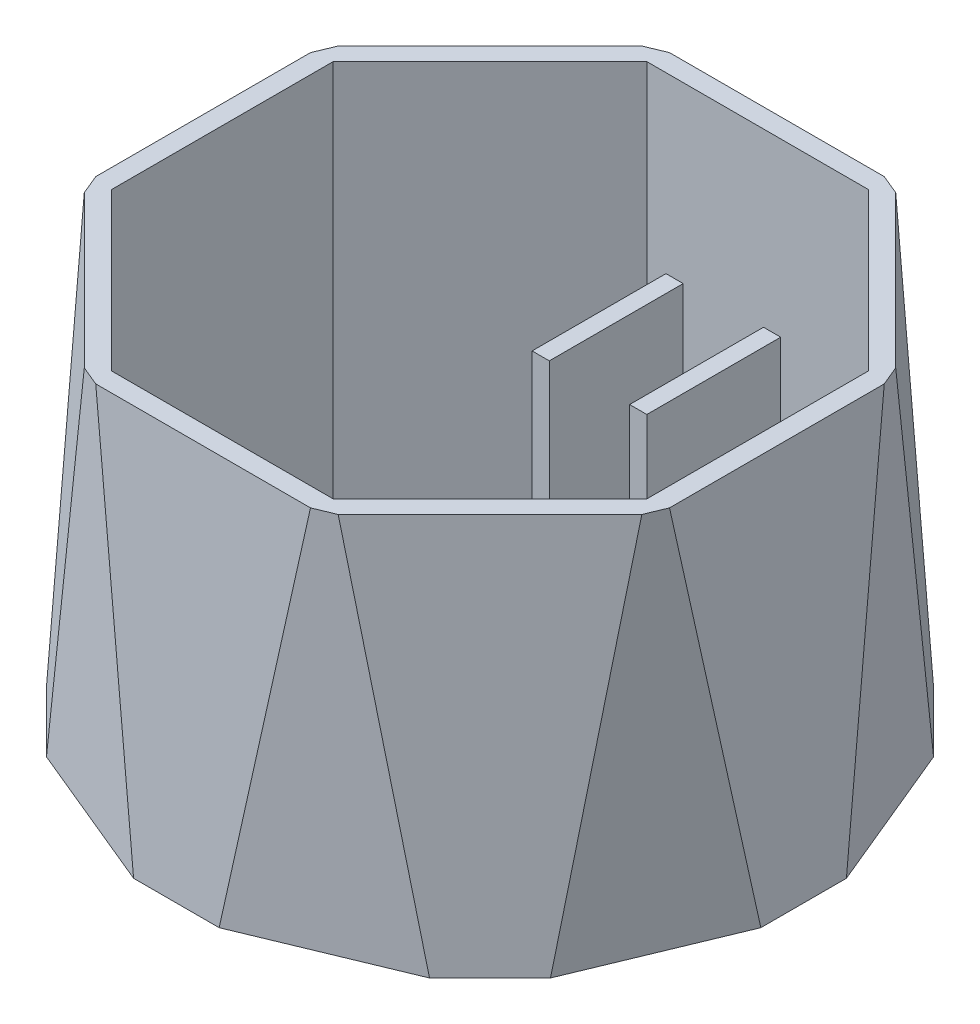
SolidWorks part; units mm, degrees
ref_plane "Front Plane" through (0, 0, 0) normal (0, 0, 1) x (1, 0, 0)
ref_plane "Top Plane" through (0, 0, 0) normal (0, 1, 0) x (1, 0, 0)
ref_plane "Right Plane" through (0, 0, 0) normal (1, 0, 0) x (0, 0, -1)
sketch "Sketch1" plane through (0, 0, 0) normal (0, 1, 0) x (1, 0, 0)
  line L0 (0, 0) -> (87.8786, 0) construction
  line L1 (75, -31.066) -> (75, 31.066)
  line L2 (75, 31.066) -> (31.066, 75)
  line L3 (31.066, 75) -> (-31.066, 75)
  line L4 (-31.066, 75) -> (-75, 31.066)
  line L5 (-75, 31.066) -> (-75, -31.066)
  line L6 (-75, -31.066) -> (-31.066, -75)
  line L7 (-31.066, -75) -> (31.066, -75)
  line L8 (31.066, -75) -> (75, -31.066)
  line L9 (70, -28.9949) -> (70, 28.9949)
  line L10 (70, 28.9949) -> (28.9949, 70)
  line L11 (28.9949, 70) -> (-28.9949, 70)
  line L12 (-28.9949, 70) -> (-70, 28.9949)
  line L13 (-70, 28.9949) -> (-70, -28.9949)
  line L14 (-70, -28.9949) -> (-28.9949, -70)
  line L15 (-28.9949, -70) -> (28.9949, -70)
  line L16 (28.9949, -70) -> (70, -28.9949)
  circle A0 centre (0, 0) radius 75 construction
  circle A1 centre (0, 0) radius 70
  dimension "D1" = 150
  dimension "D2" = 5
extrude "Boss-Extrude2" add sketch "Sketch1" along normal blind 100 contours L7 L8 L1 L2 L3 L4 L5 L6 L16 L15 L14 L13 L12 L11 L10 L9
sketch "Sketch2" plane through (0, 0, -70) normal (0, 0, 1) x (1, 0, 0)
  line L0 (28.9949, 0) -> (-28.9949, 0) construction
  line L1 (-23.9949, 0) -> (-19.4949, 0)
  line L2 (-23.9949, 0) -> (-23.9949, 54.5)
  line L3 (-23.9949, 54.5) -> (-19.4949, 54.5)
  line L4 (-19.4949, 0) -> (-19.4949, 54.5)
  line L5 (-8.9949, 0) -> (-8.9949, 40.2673) construction
  line L10 (6.0051, 55.1109) -> (1.5051, 55.1109)
  line L11 (1.5051, 0.6109) -> (1.5051, 55.1109)
  line L12 (6.0051, 0.6109) -> (1.5051, 0.6109)
  line L13 (6.0051, 0.6109) -> (6.0051, 55.1109)
  dimension "D1" = 4.5
  dimension "D2" = 54.5
  dimension "D3" = 20
  dimension "D4" = 10.5
  dimension "D5" = 10.5
extrude "Boss-Extrude3" add sketch "Sketch2" along normal blind 35
chamfer "Chamfer1" distance 3 8 edges at (31.066, 50, -75) (-31.066, 50, -75) (-75, 50, -31.066) (-75, 50, 31.066) (-31.066, 50, 75) (31.066, 50, 75) (75, 50, 31.066) (75, 50, -31.066)
draft "Draft2" type of draft neutral plane draft angle 4 faces to draft 8 face at (53.033, 50, -53.033) face at (0, 50, -75) face at (-53.033, 50, -53.033) face at (-75, 50, 0) face at (-53.033, 50, 53.033) face at (0, 50, 75) face at (53.033, 50, 53.033) face at (75, 50, 0) neutral plane through (0, 100, 0) neutral plane normal (0, 1, 0) parameters "D1"=4
